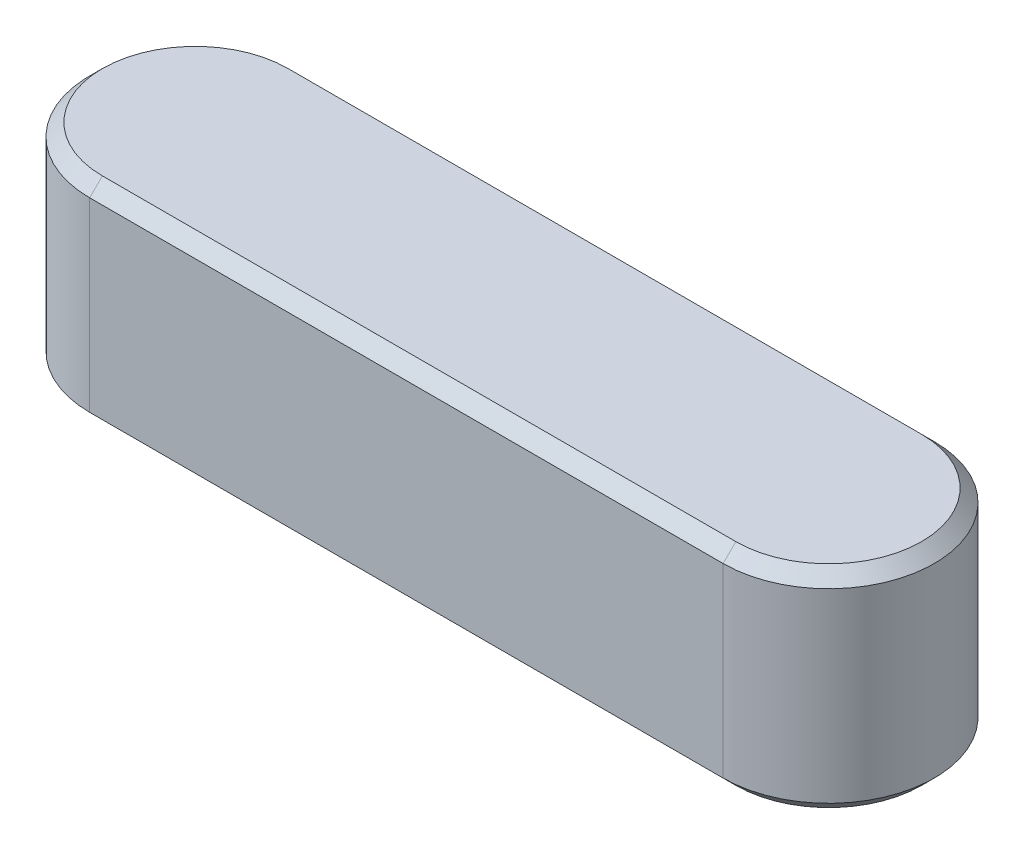
SolidWorks part; units mm, degrees
ref_plane "Front" through (0, 0, 0) normal (0, 0, 1) x (1, 0, 0)
ref_plane "Top" through (0, 0, 0) normal (0, 1, 0) x (1, 0, 0)
ref_plane "Right" through (0, 0, 0) normal (1, 0, 0) x (0, 0, -1)
sketch "Sketch1" plane through (0, 0, 0) normal (0, 1, 0) x (1, 0, 0)
  line L0 (0, 0) -> (15, 0) construction
  line L1 (0, 2.5) -> (15, 2.5)
  line L2 (0, -2.5) -> (15, -2.5)
  arc A0 (0, 2.5) -> (0, -2.5) centre (0, 0) ccw
  arc A1 (15, -2.5) -> (15, 2.5) centre (15, 0) ccw
  point P3 (7.5, 0)
  dimension "D2" = 2.5
  dimension "D1" = 15
extrude "Boss-Extrude1" add sketch "Sketch1" along normal blind 5
chamfer "Chamfer1" distance 0.3 angle 45 8 edges at (7.5, 0, 2.5) (17.5, 0, 0) (7.5, 0, -2.5) (-2.5, 0, 0) (7.5, 5, -2.5) (17.5, 5, 0) (7.5, 5, 2.5) (-2.5, 5, 0)
